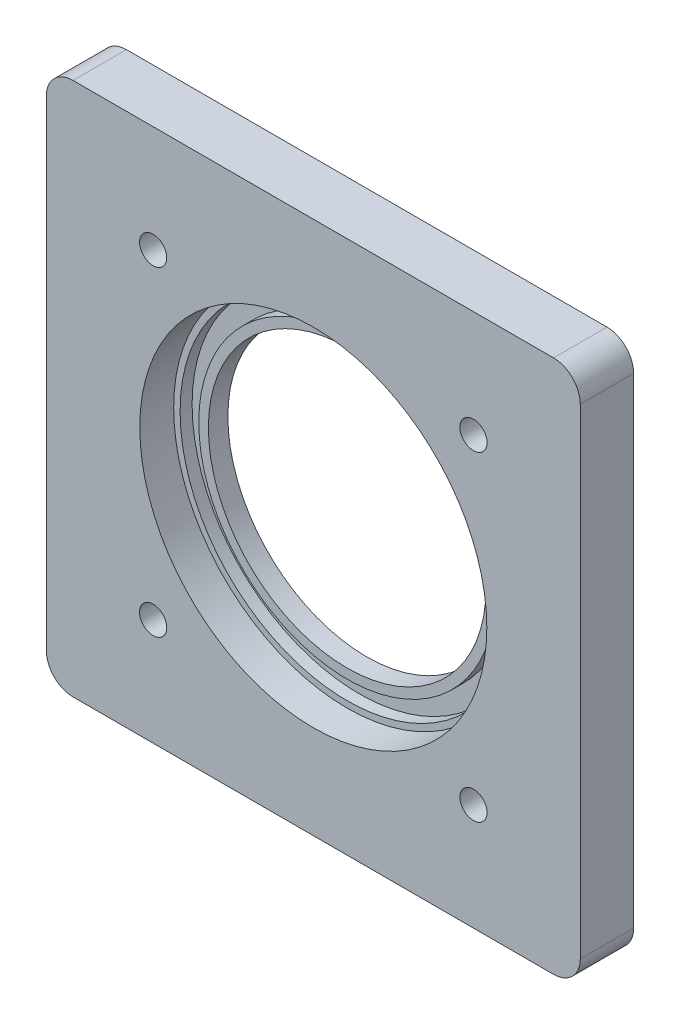
SolidWorks part; units mm, degrees
ref_plane "Front Plane" through (0, 0, 0) normal (0, 0, 1) x (1, 0, 0)
ref_plane "Top Plane" through (0, 0, 0) normal (0, 1, 0) x (1, 0, 0)
ref_plane "Right Plane" through (0, 0, 0) normal (1, 0, 0) x (0, 0, -1)
ref_plane "Plane1" through (0, 0, 0) normal (0, 0, -1) x (-1, 0, 0)
sketch "Sketch1" plane through (0, 0, 0) normal (0, 0, -1) x (-1, 0, 0)
  line L0 (-100, 0) -> (0, 0)
  line L1 (0, 0) -> (0, 100)
  line L2 (0, 100) -> (-100, 100)
  line L3 (-100, 100) -> (-100, 0)
extrude "Boss-Extrude1" add sketch "Sketch1" against normal blind 10
hole_wizard "Hole1" positions "Sketch3" profile "Sketch2" legacy
sketch "Sketch3" plane through (0, 0, 10) normal (0, 0, 1) x (1, 0, 0)
  point P0 (50, 50)
sketch "Sketch2" plane through (50, 50, 10) normal (1, 0, 0) x (0, -1, 0)
  line L0 (0, 0) -> (0, 8.6)
  line L1 (0, 8.6) -> (31.3, 8.6)
  line L2 (31.3, 8.6) -> (31.3, 0)
  line L3 (31.3, 0) -> (0, 0)
  line L4 (0, 110) -> (0, -10) construction
  dimension "Diameter" = 62.6
  dimension "Depth" = 8.6
ref_plane "Plane2" through (0, 50, 0) normal (0, -1, 0) x (1, 0, 0)
sketch "Sketch4" plane through (0, 50, 0) normal (0, -1, 0) x (1, 0, 0)
  line L0 (77.8, 3.65) -> (50, 3.65)
  line L1 (50, 3.65) -> (50, 1.4)
  line L2 (50, 1.4) -> (77.8, 1.4)
  line L3 (77.8, 1.4) -> (77.8, 3.65)
  line L4 (50, 3.65) -> (50, 1.4) construction
revolve "Revolve1" add sketch "Sketch4" angle 360 about L4
sketch "Sketch5" plane through (0, 50, 0) normal (0, -1, 0) x (1, 0, 0)
  line L0 (82.5, 10) -> (81.3, 10)
  line L1 (81.3, 10) -> (81.3, 3.65)
  line L2 (81.3, 3.65) -> (82.5, 3.65)
  line L3 (82.5, 3.65) -> (82.5, 10)
  line L4 (50, 10) -> (50, 3.65) construction
revolve "Cut-Revolve1" cut sketch "Sketch5" angle 360 about L4
hole_wizard "#10 Clearance Hole1" positions "Sketch7" profile "Sketch6" hole size "#10" standard "ANSI Inch"
sketch "Sketch7" plane through (0, 0, 10) normal (0, 0, 1) x (1, 0, 0)
  point P0 (80, 80)
  point P1 (80, 20)
  point P2 (20, 20)
  point P3 (20, 80)
sketch "Sketch6" plane through (80, 80, 10) normal (1, 0, 0) x (0, -1, 0)
  line L0 (0, 0) -> (0, 6)
  line L1 (0, 6) -> (2.55, 6)
  line L2 (2.55, 6) -> (2.55, 0)
  line L5 (2.55, 0) -> (0, 0)
  line L10 (0, 6) -> (-2.55, 6) construction
  line L11 (0, -6.35) -> (0, 107.95) construction
  dimension "Hole Dia." = 5.1
  dimension "Hole Depth" = 6
  dimension "Drill Angle" = 180
hole_wizard "Hole2" positions "Sketch9" profile "Sketch8" legacy
sketch "Sketch9" plane through (0, 0, 3.65) normal (0, 0, 1) x (1, 0, 0)
  point P0 (50, 50)
sketch "Sketch8" plane through (50, 50, 3.65) normal (1, 0, 0) x (0, -1, 0)
  line L0 (0, 0) -> (0, 3.65)
  line L1 (0, 3.65) -> (26, 3.65)
  line L2 (26, 3.65) -> (26, 0)
  line L3 (26, 0) -> (0, 0)
  line L4 (0, 110) -> (0, -10) construction
  dimension "Diameter" = 52
  dimension "Depth" = 3.65
fillet "Fillet1" radius 5 4 edges at (0, 0, 5) (0, 100, 5) (100, 100, 5) (100, 0, 5)
